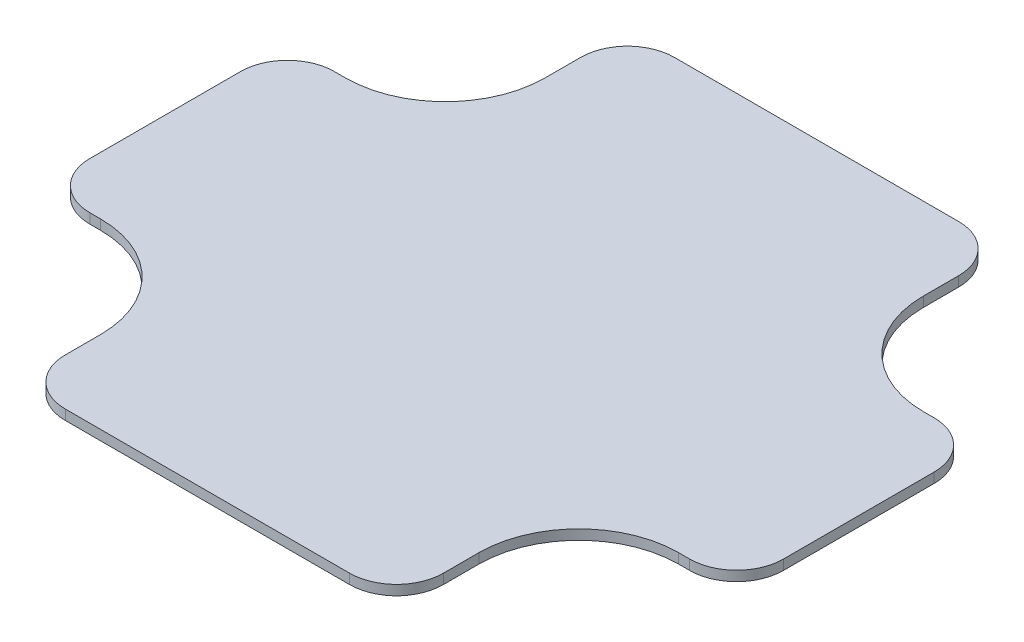
SolidWorks part; units mm, degrees
ref_plane "Front Plane" through (0, 0, 0) normal (0, 0, 1) x (1, 0, 0)
ref_plane "Top Plane" through (0, 0, 0) normal (0, 1, 0) x (1, 0, 0)
ref_plane "Right Plane" through (0, 0, 0) normal (1, 0, 0) x (0, 0, -1)
sketch "Sketch1" plane through (0, 0, 0) normal (0, 1, 0) x (1, 0, 0)
  line L0 (-96, 39.1323) -> (-92.5, 39.1324)
  line L1 (-45.5, -97.4686) -> (45.5, -97.4686)
  line L3 (-45.5, 97.4686) -> (45.5, 97.4685)
  line L5 (-45.5, -97.4686) -> (45.5, 97.4685) construction
  line L6 (-45.5, 97.4686) -> (45.5, -97.4686) construction
  line L8 (-111, -24.1323) -> (-111, 24.1323)
  line L10 (111, -24.1324) -> (111, 24.1324)
  line L11 (-111, -24.1323) -> (111, 24.1324) construction
  line L12 (-111, 24.1323) -> (111, -24.1324) construction
  line L13 (-60.5, 71.1324) -> (-60.5, 82.4686)
  line L14 (0, 192.2328) -> (0, -194.3769) construction
  line L15 (-111, 0) -> (111, 0) construction
  line L16 (96, 39.1324) -> (92.5, 39.1324)
  line L17 (60.5, 71.1324) -> (60.5, 82.4686)
  line L18 (96, -39.1324) -> (92.5, -39.1324)
  line L19 (60.5, -71.1324) -> (60.5, -82.4686)
  line L20 (-60.5, -71.1324) -> (-60.5, -82.4686)
  line L21 (-96, -39.1323) -> (-92.5, -39.1324)
  arc A0 (-111, 24.1323) -> (-96, 39.1323) centre (-96, 24.1323) cw
  arc A1 (-92.5, 39.1324) -> (-60.5, 71.1324) centre (-92.5, 71.1324) ccw
  arc A2 (-60.5, 82.4686) -> (-45.5, 97.4686) centre (-45.5, 82.4686) cw
  arc A3 (111, 24.1324) -> (96, 39.1324) centre (96, 24.1324) ccw
  arc A4 (92.5, 39.1324) -> (60.5, 71.1324) centre (92.5, 71.1324) cw
  arc A5 (60.5, 82.4686) -> (45.5, 97.4685) centre (45.5, 82.4686) ccw
  arc A6 (111, -24.1324) -> (96, -39.1324) centre (96, -24.1324) cw
  arc A7 (92.5, -39.1324) -> (60.5, -71.1324) centre (92.5, -71.1324) ccw
  arc A8 (60.5, -82.4686) -> (45.5, -97.4686) centre (45.5, -82.4686) cw
  arc A9 (-60.5, -82.4686) -> (-45.5, -97.4686) centre (-45.5, -82.4686) ccw
  arc A10 (-92.5, -39.1324) -> (-60.5, -71.1324) centre (-92.5, -71.1324) cw
  arc A11 (-111, -24.1323) -> (-96, -39.1323) centre (-96, -24.1323) ccw
  point P0 (0, 0)
  point P6 (0, 0)
  dimension "D1" = 15
  dimension "D2" = 15
  dimension "D3" = 32
  dimension "D4" = 3.5
  dimension "D5" = 91
  dimension "D6" = 48.2647
  dimension "D7" = 11.3362
extrude "Boss-Extrude1" add sketch "Sketch1" along normal blind 3.175
